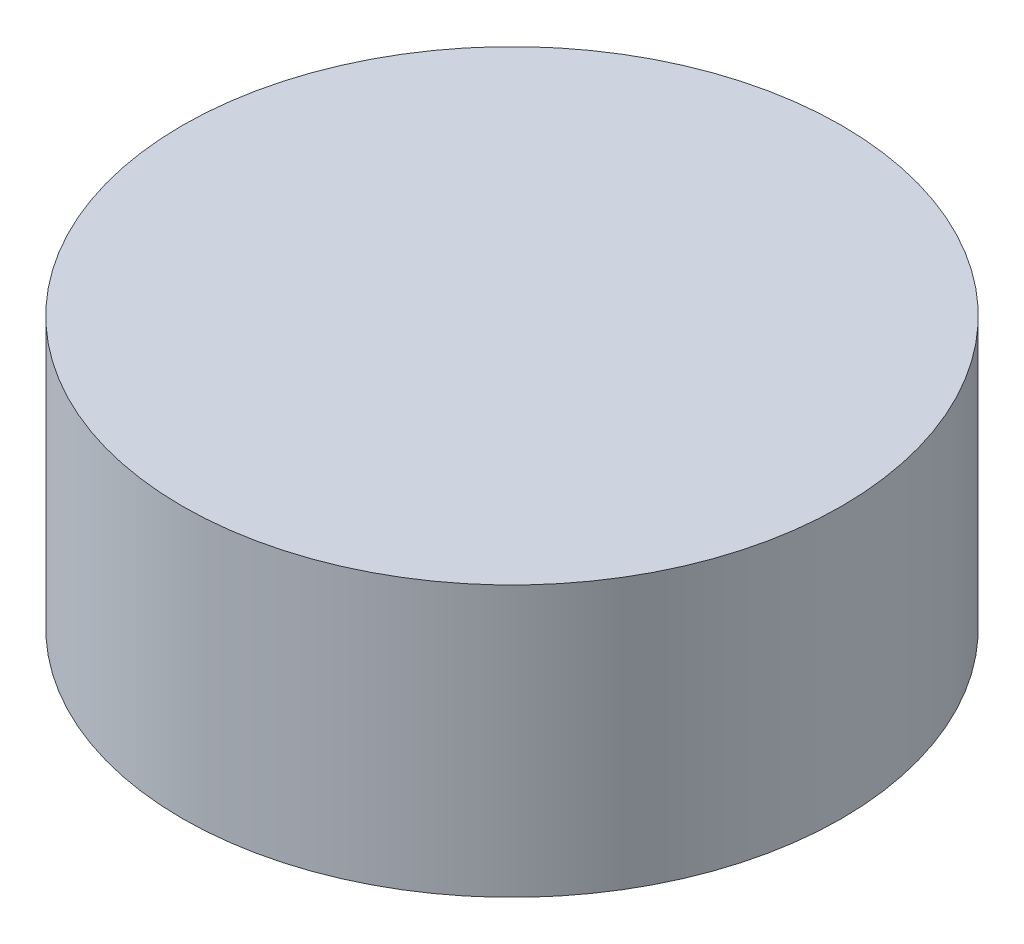
SolidWorks part; units mm, degrees
ref_plane "Front Plane" through (0, 0, 0) normal (0, 0, 1) x (1, 0, 0)
ref_plane "Top Plane" through (0, 0, 0) normal (0, 1, 0) x (1, 0, 0)
ref_plane "Right Plane" through (0, 0, 0) normal (1, 0, 0) x (0, 0, -1)
sketch "Sketch1" plane through (0, 0, 0) normal (0, 1, 0) x (1, 0, 0)
  line L0 (0, 0) -> (0, 8.114) construction
  line L1 (0, 8.114) -> (0, 0) construction
  line L2 (0, 0) -> (11.3236, 0) construction
  circle A0 centre (3.9, 3.9) radius 3.9
  dimension "D1" = 7.8
extrude "Boss-Extrude1" add sketch "Sketch1" against normal blind 3.2
shell "Shell1" thickness 1.3
